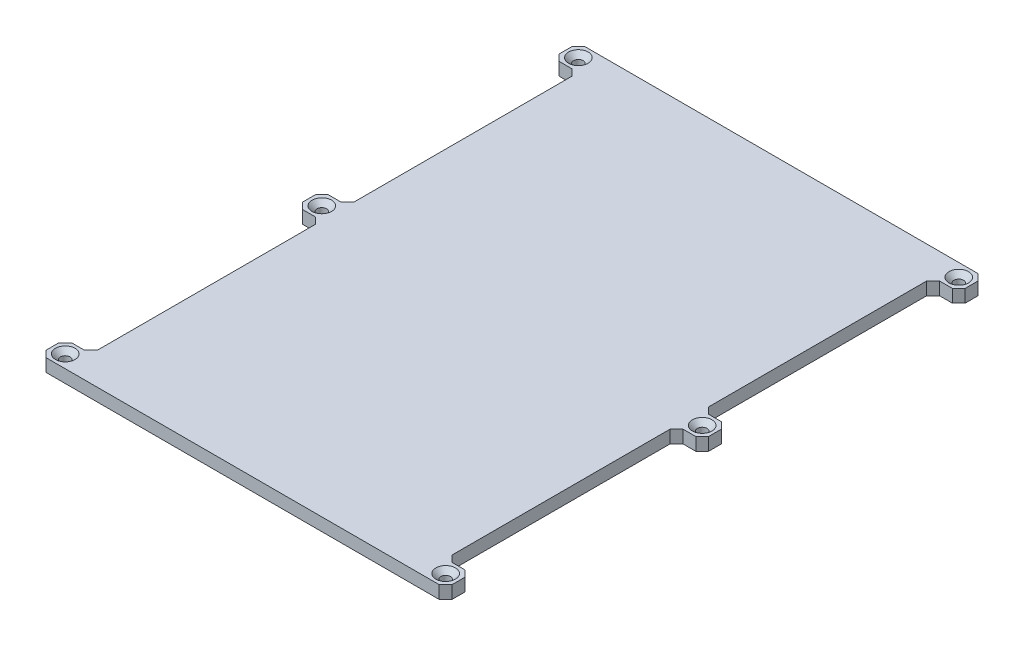
SolidWorks part; units mm, degrees
ref_plane "Front Plane" through (0, 0, 0) normal (0, 0, 1) x (1, 0, 0)
ref_plane "Top Plane" through (0, 0, 0) normal (0, 1, 0) x (1, 0, 0)
ref_plane "Right Plane" through (0, 0, 0) normal (1, 0, 0) x (0, 0, -1)
sketch "Sketch1" plane through (0, 0, 0) normal (0, 1, 0) x (1, 0, 0)
  line L0 (0, 84) -> (110.6, 84) construction
  line L1 (0, 0) -> (110.6, 0)
  line L2 (0, 8) -> (0, 80)
  line L3 (0, 168) -> (110.6, 168)
  line L4 (110.6, 8) -> (110.6, 80)
  line L5 (110.6, 88) -> (110.6, 160)
  line L6 (110.6, 88) -> (118.6, 88)
  line L8 (110.6, 80) -> (118.6, 80)
  line L9 (118.6, 88) -> (118.6, 80)
  line L10 (110.6, 168) -> (118.6, 168)
  line L12 (110.6, 160) -> (118.6, 160)
  line L13 (118.6, 168) -> (118.6, 160)
  line L14 (110.6, 0) -> (118.6, 0)
  line L16 (110.6, 8) -> (118.6, 8)
  line L17 (118.6, 0) -> (118.6, 8)
  line L18 (55.3, 168) -> (55.3, 0) construction
  line L19 (0, 0) -> (-8, 0)
  line L20 (-8, 0) -> (-8, 8)
  line L21 (0, 8) -> (-8, 8)
  line L22 (0, 80) -> (-8, 80)
  line L23 (-8, 88) -> (-8, 80)
  line L24 (0, 88) -> (-8, 88)
  line L25 (0, 160) -> (-8, 160)
  line L26 (-8, 168) -> (-8, 160)
  line L27 (0, 168) -> (-8, 168)
  line L28 (0, 88) -> (0, 160)
  line L29 (0, 124) -> (110.6, 124) construction
  line L30 (0, 44) -> (110.6, 44) construction
  circle A0 centre (114.6, 164) radius 1.5
  circle A1 centre (114.6, 84) radius 1.5
  circle A2 centre (114.6, 4) radius 1.5
  circle A3 centre (-4, 4) radius 1.5
  circle A4 centre (-4, 84) radius 1.5
  circle A5 centre (-4, 164) radius 1.5
  point P32 (114.6, 168)
  point P34 (118.6, 164)
  dimension "D9" = 3
  dimension "D1" = 110.6
  dimension "D2" = 168
  dimension "D3" = 8
  dimension "D4" = 8
  dimension "D5" = 8
  dimension "D6" = 8
  dimension "D7" = 8
  dimension "D8" = 8
extrude "Boss-Extrude1" add sketch "Sketch1" along normal blind 4
chamfer "Chamfer1" distance 2 angle 45 20 edges at (0, 2, -80) (-8, 2, -80) (0, 2, -88) (-8, 2, -88) (0, 2, -8) (-8, 2, -8) (-8, 2, 0) (118.6, 2, 0) (118.6, 2, -8) (110.6, 2, -8) (110.6, 2, -88) (118.6, 2, -88) (118.6, 2, -80) (110.6, 2, -80) (118.6, 2, -168) (118.6, 2, -160) (110.6, 2, -160) (0, 2, -160) (-8, 2, -160) (-8, 2, -168)
chamfer "Chamfer2" distance 1.55 angle 45 6 edges at (114.6, 4, -2.5) (-4, 4, -5.5) (-4, 4, -82.5) (114.6, 4, -85.5) (114.6, 4, -162.5) (-4, 4, -165.5)
